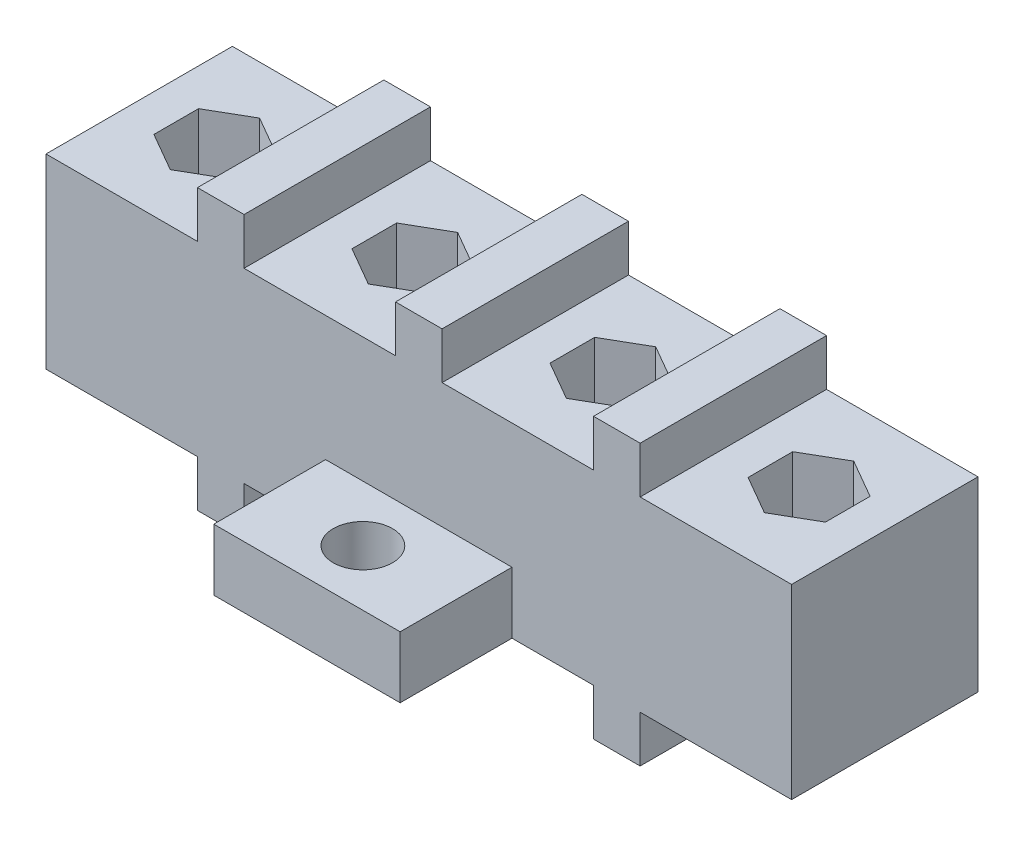
SolidWorks part; units mm, degrees
ref_plane "Front Plane" through (0, 0, 0) normal (0, 0, 1) x (1, 0, 0)
ref_plane "Top Plane" through (0, 0, 0) normal (0, 1, 0) x (1, 0, 0)
ref_plane "Right Plane" through (0, 0, 0) normal (1, 0, 0) x (0, 0, -1)
sketch "Sketch1" plane through (0, 0, 0) normal (0, 1, 0) x (1, 0, 0)
  line L1 (25.4, 6.35) -> (-25.4, 6.35)
  line L2 (25.4, 6.35) -> (25.4, -6.35)
  line L3 (25.4, -6.35) -> (-25.4, -6.35)
  line L4 (-25.4, 6.35) -> (-25.4, -6.35)
  line L5 (25.4, 6.35) -> (-25.4, -6.35) construction
  line L6 (25.4, -6.35) -> (-25.4, 6.35) construction
  point P0 (0, 0)
  dimension "D1" = 50.8
  dimension "D2" = 12.7
extrude "Boss-Extrude1" add sketch "Sketch1" along normal mid plane 12.7
ref_plane "Plane1" through (0, 0, 0) normal (0, 1, 0) x (1, 0, 0)
sketch "Sketch9" plane through (0, 6.35, 0) normal (0, 1, 0) x (1, 0, 0)
  line L0 (-25.4, -6.35) -> (25.4, -6.35) construction
  line L1 (-15.0813, -6.35) -> (-11.9063, -6.35)
  line L2 (-15.0813, -6.35) -> (-15.0813, 6.35)
  line L3 (-15.0813, 6.35) -> (-11.9063, 6.35)
  line L4 (-11.9063, -6.35) -> (-11.9063, 6.35)
  line L5 (25.4, 6.35) -> (-25.4, 6.35) construction
  line L6 (-9.2075, 0) -> (-17.78, 0) construction
  line L7 (-15.0813, 0) -> (-11.9063, 0)
  line L8 (-9.2075, 6.35) -> (-9.2075, -6.35) construction
  line L9 (-25.4, 6.35) -> (-25.4, -6.35) construction
  point P14 (-13.4938, 0)
  dimension "D1" = 3.175
  dimension "D2" = 10.3187
extrude "Boss-Extrude3" add sketch "Sketch9" along normal blind 3.175 contours L2 L3 L4 L1
pattern_linear "LPattern1" count 3 spacing 13.4937 along (1, 0, 0) of "Boss-Extrude3"
mirror "Mirror2" about plane through (0, 0, 0) normal (0, 1, 0) of "LPattern1", "Boss-Extrude3"
sketch "Sketch10" plane through (0, 6.35, 0) normal (0, 1, 0) x (1, 0, 0)
  line L7 (-10.4775, 0) -> (10.4775, 0) construction
  line L8 (-17.6054, 1.5215) -> (-20.2406, 3.0429)
  line L9 (-20.2406, 3.0429) -> (-22.8759, 1.5215)
  line L10 (-22.8759, 1.5215) -> (-22.8759, -1.5215)
  line L11 (-22.8759, -1.5215) -> (-20.2406, -3.0429)
  line L12 (-20.2406, -3.0429) -> (-17.6054, -1.5215)
  line L13 (-17.6054, -1.5215) -> (-17.6054, 1.5215)
  line L14 (-15.0813, -6.35) -> (-15.0812, 6.35) construction
  line L15 (-25.4, 6.35) -> (-25.4, -6.35) construction
  line L16 (-25.4, 6.35) -> (-25.4, -6.35) construction
  line L17 (-15.0812, 6.35) -> (-25.4, 6.35) construction
  line L18 (-25.4, 0) -> (-15.0813, 0) construction
  line L19 (-15.0813, -6.35) -> (-15.0812, 6.35) construction
  circle A0 centre (-20.2406, 0) radius 2.6352 construction
  dimension "D1" = 5.2705
extrude "Cut-Extrude1" cut sketch "Sketch10" against normal blind 9.525
pattern_linear "LPattern2" count 4 spacing 13.4937 along (1, 0, 0) of "Cut-Extrude1"
hole_wizard "#4 Clearance Hole2" positions "Sketch11" profile "Sketch12" hole size "#4" standard "ANSI Inch" end condition through all
sketch "Sketch11" plane through (0, -3.175, 0) normal (0, 1, 0) x (1, 0, 0)
  line L0 (-22.8759, 0) -> (-17.6054, 0) construction
  line L1 (-22.8759, 1.5215) -> (-22.8759, -1.5215) construction
  line L2 (-17.6054, -1.5215) -> (-17.6054, 1.5215) construction
  point P0 (-20.2406, 0)
sketch "Sketch12" plane through (-20.2406, -3.175, 0) normal (1, 0, 0) x (0, 0, 1)
  line L0 (0, 0) -> (0, 6.35)
  line L1 (0, 6.35) -> (1.4732, 6.35)
  line L2 (1.4732, 6.35) -> (1.4732, 0)
  line L5 (1.4732, 0) -> (0, 0)
  line L11 (0, -6.35) -> (0, 107.95) construction
  dimension "Thru Hole Dia." = 2.9464
  dimension "Thru Hole Depth" = 6.35
pattern_linear "LPattern3" count 4 spacing 13.4937 along (1, 0, 0) of "#4 Clearance Hole2"
sketch "Sketch13" plane through (0, 0, 6.35) normal (0, 0, 1) x (1, 0, 0)
  line L0 (0, -6.985) -> (0, 6.985) construction
  line L1 (6.35, -6.35) -> (-6.35, -6.35)
  line L2 (6.35, -6.35) -> (6.35, -2.159)
  line L3 (6.35, -2.159) -> (-6.35, -2.159)
  line L4 (-6.35, -6.35) -> (-6.35, -2.159)
  line L5 (6.35, -6.35) -> (-6.35, -2.159) construction
  line L6 (6.35, -2.159) -> (-6.35, -6.35) construction
  line L11 (1.5875, -6.35) -> (11.9062, -6.35) construction
  point P0 (0, -4.2545)
  dimension "D1" = 4.191
  dimension "D2" = 12.7
extrude "Boss-Extrude4" add sketch "Sketch13" along normal blind 7.62 contours L3 L4 L1 L2
hole_wizard "Hole1" positions "Sketch14" profile "Sketch15" legacy end condition through all
sketch "Sketch14" plane through (0, -2.159, 0) normal (0, 1, 0) x (1, 0, 0)
  line L0 (0, -10.4775) -> (0, 10.4775) construction
  line L1 (6.35, -6.35) -> (-6.35, -6.35) construction
  line L2 (4.1932, -13.97) -> (4.1932, -6.35)
  line L3 (6.35, -13.97) -> (-6.35, -13.97) construction
  point P0 (0, -10.16)
  dimension "D1" = 7.62
  dimension "D2" = 3.81
sketch "Sketch15" plane through (0, -2.159, 10.16) normal (1, 0, 0) x (0, 0, 1)
  line L0 (0, 0) -> (0, 7.366)
  line L1 (0, 7.366) -> (2.0193, 7.366)
  line L2 (2.0193, 7.366) -> (2.0193, 0)
  line L5 (2.0193, 0) -> (0, 0)
  line L11 (0, -6.35) -> (0, 107.95) construction
  dimension "Thru Hole Dia." = 4.0386
  dimension "Thru Hole Depth" = 7.366
mirror "Mirror4" about plane through (0, 0, 0) normal (0, 0, 1) of "Boss-Extrude4", "Hole1"
equation "\"D2@Sketch14\"=\"D1@Sketch14\"/2"
